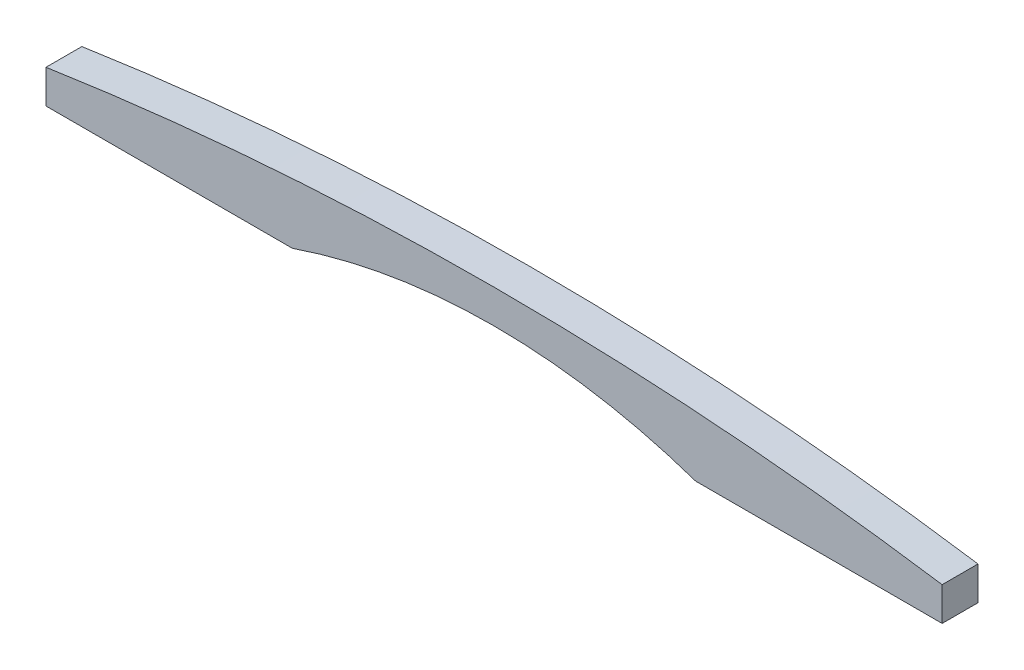
SolidWorks part; units mm, degrees
ref_plane "Plan de face" through (0, 0, 0) normal (0, 0, 1) x (1, 0, 0)
ref_plane "Plan de dessus" through (0, 0, 0) normal (0, 1, 0) x (1, 0, 0)
ref_plane "Plan de droite" through (0, 0, 0) normal (1, 0, 0) x (0, 0, -1)
sketch "Esquisse1" plane through (0, 0, 0) normal (0, 0, 1) x (1, 0, 0)
  line L0 (-100, 0) -> (100, 0) construction
  line L1 (-100, 0) -> (-100, 7.5)
  line L2 (100, 0) -> (100, 7.5)
  line L3 (-100, 0) -> (-45, 0)
  line L4 (100, 0) -> (45, 0)
  line L5 (-100, 7.5) -> (100, 7.5) construction
  line L6 (0, 0) -> (0, 15) construction
  line L7 (-90, 15) -> (-10, 15) construction
  arc A0 (-45, 0) -> (45, 0) centre (0, -131.25) cw
  arc A1 (-100, 7.5) -> (100, 7.5) centre (0, -655.4167) cw
  dimension "D1" = 200
  dimension "D2" = 7.5
  dimension "D3" = 7.5
  dimension "D4" = 55
  dimension "D5" = 55
extrude "Boss.-Extru.1" add sketch "Esquisse1" along normal blind 8
